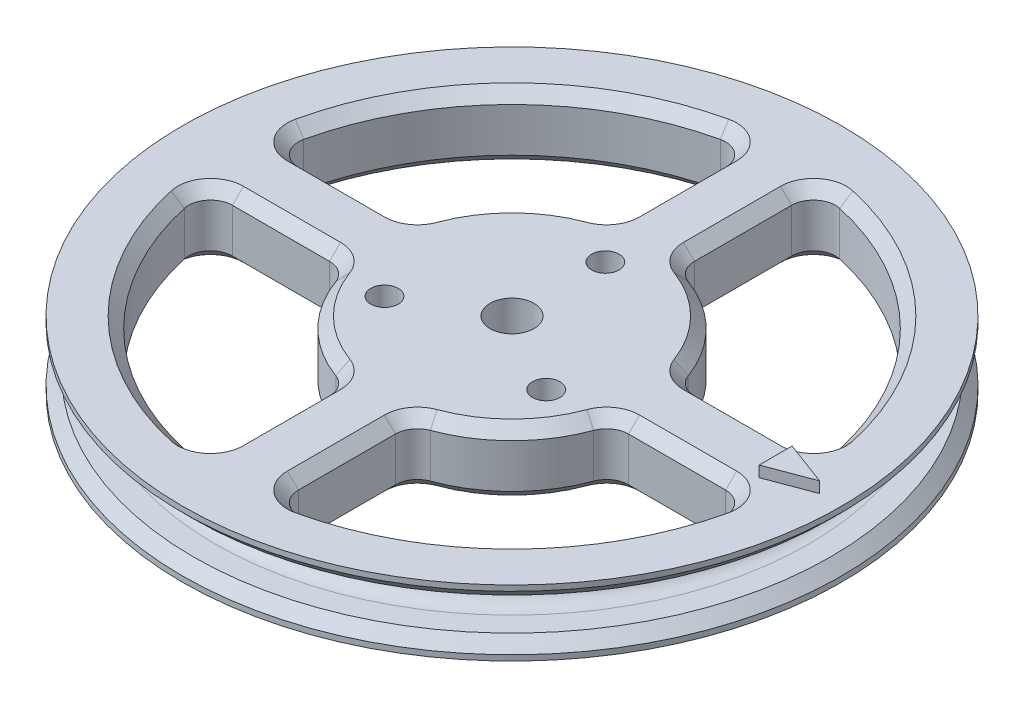
SolidWorks part; units mm, degrees
ref_plane "Front Plane" through (0, 0, 0) normal (0, 0, 1) x (1, 0, 0)
ref_plane "Top Plane" through (0, 0, 0) normal (0, 1, 0) x (1, 0, 0)
ref_plane "Right Plane" through (0, 0, 0) normal (1, 0, 0) x (0, 0, -1)
sketch "Sketch1" plane through (0, 0, 0) normal (0, 1, 0) x (1, 0, 0)
  line L0 (0, 0) -> (0, 36.3748) construction
  line L1 (0, 0) -> (-45.1254, 0) construction
  line L2 (-22.4499, -3) -> (-13.6107, -3)
  line L3 (-3, -22.4499) -> (-3, -13.6107)
  line L4 (3, -22.4499) -> (3, -13.6107)
  line L5 (22.4499, -3) -> (13.6107, -3)
  line L6 (22.4499, 3) -> (13.6107, 3)
  line L7 (3, 22.4499) -> (3, 13.6107)
  line L8 (-3, 22.4499) -> (-3, 13.6107)
  line L9 (-22.4499, 3) -> (-13.6107, 3)
  circle A0 centre (0, 0) radius 30
  circle A1 centre (0, 0) radius 8.5 construction
  circle A3 centre (0, 0) radius 2
  circle A4 centre (-7.3612, -4.25) radius 1.5 construction
  circle A5 centre (7.3612, -4.25) radius 1.5 construction
  circle A6 centre (0, 8.5) radius 1.5 construction
  arc A7 (-24.4021, -5.4348) -> (-5.4348, -24.4021) centre (0, 0) ccw
  arc A8 (-11.7333, -4.3103) -> (-4.3103, -11.7333) centre (0, 0) ccw
  arc A9 (0, -12.5) -> (-12.5, 0) centre (0, 0) ccw construction
  arc A10 (0, -25) -> (-25, 0) centre (0, 0) ccw construction
  arc A11 (-13.6107, -3) -> (-11.7333, -4.3103) centre (-13.6107, -5) cw
  arc A12 (-4.3103, -11.7333) -> (-3, -13.6107) centre (-5, -13.6107) cw
  arc A13 (-3, -22.4499) -> (-5.4348, -24.4021) centre (-5, -22.4499) cw
  arc A14 (-24.4021, -5.4348) -> (-22.4499, -3) centre (-22.4499, -5) cw
  arc A15 (24.4021, -5.4348) -> (5.4348, -24.4021) centre (0, 0) cw
  arc A16 (3, -22.4499) -> (5.4348, -24.4021) centre (5, -22.4499) ccw
  arc A17 (4.3103, -11.7333) -> (3, -13.6107) centre (5, -13.6107) ccw
  arc A18 (11.7333, -4.3103) -> (4.3103, -11.7333) centre (0, 0) cw
  arc A19 (13.6107, -3) -> (11.7333, -4.3103) centre (13.6107, -5) ccw
  arc A20 (24.4021, -5.4348) -> (22.4499, -3) centre (22.4499, -5) ccw
  arc A21 (24.4021, 5.4348) -> (22.4499, 3) centre (22.4499, 5) cw
  arc A22 (13.6107, 3) -> (11.7333, 4.3103) centre (13.6107, 5) cw
  arc A23 (11.7333, 4.3103) -> (4.3103, 11.7333) centre (0, 0) ccw
  arc A24 (4.3103, 11.7333) -> (3, 13.6107) centre (5, 13.6107) cw
  arc A25 (3, 22.4499) -> (5.4348, 24.4021) centre (5, 22.4499) cw
  arc A26 (24.4021, 5.4348) -> (5.4348, 24.4021) centre (0, 0) ccw
  arc A27 (-24.4021, 5.4348) -> (-5.4348, 24.4021) centre (0, 0) cw
  arc A28 (-3, 22.4499) -> (-5.4348, 24.4021) centre (-5, 22.4499) ccw
  arc A29 (-4.3103, 11.7333) -> (-3, 13.6107) centre (-5, 13.6107) ccw
  arc A30 (-11.7333, 4.3103) -> (-4.3103, 11.7333) centre (0, 0) cw
  arc A31 (-13.6107, 3) -> (-11.7333, 4.3103) centre (-13.6107, 5) ccw
  arc A32 (-24.4021, 5.4348) -> (-22.4499, 3) centre (-22.4499, 5) ccw
  point P4 (0, 8.5)
  point P5 (7.3612, -4.25)
  point P8 (-7.3612, -4.25)
  point P9 (0, 0)
  dimension "D1" = 60
  dimension "D2" = 17
  dimension "D4" = 4
  dimension "D5" = 3
  dimension "D6" = 50
  dimension "D7" = 25
  dimension "D10" = 2
  dimension "D8" = 3
  dimension "D9" = 3
  dimension "D3" = 3
extrude "Boss-Extrude1" add sketch "Sketch1" along normal blind 6
hole_wizard "M3x0.5 Tapped Hole1" positions "Sketch3" profile "Sketch4" tap size "M3x0.5" standard "ANSI Metric" end condition through all
sketch "Sketch3" plane through (0, 6, 0) normal (0, 1, 0) x (1, 0, 0)
  circle A0 centre (0, 0) radius 8.5 construction
  point P7 (0, 8.5)
  point P14 (7.3612, -4.25)
  point P15 (-7.3612, -4.25)
  dimension "D1" = 17
  dimension "D2" = 3
cosmetic thread "Hole Thread1" parameters "D2"=3
cosmetic thread "Hole Thread2" parameters "D2"=3
cosmetic thread "Hole Thread3" parameters "D2"=3
sketch "Sketch4" plane through (-7.3612, 6, 4.25) normal (1, 0, 0) x (0, 0, 1)
  line L0 (0, 0) -> (0, 6)
  line L1 (0, 6) -> (1.25, 6)
  line L2 (1.25, 6) -> (1.25, 0)
  line L5 (1.25, 0) -> (0, 0)
  line L11 (0, -6.35) -> (0, 107.95) construction
  dimension "Thru Tap Drill Dia." = 2.5
  dimension "Thru Tap Drill Depth" = 6
sketch "Sketch5" plane through (0, 0, 0) normal (1, 0, 0) x (0, 0, -1)
  line L0 (-30, 4.5) -> (-27, 4.5)
  line L1 (-30, 6) -> (-30, 0) construction
  line L2 (-30, 1.5) -> (-27, 1.5)
  line L3 (-30, 1.5) -> (-30, 4.5)
  line L4 (-30, 6) -> (-30, 3) construction
  line L5 (0, 0) -> (0, 13.1022) construction
  arc A1 (-27, 1.5) -> (-27, 4.5) centre (-27, 3) ccw
  point P9 (-30, 3)
  dimension "D3" = 3
  dimension "D1" = 3
  dimension "D2" = 3
revolve "Cut-Revolve1" cut sketch "Sketch5" angle 360 about L5
chamfer "Chamfer1" distance 1 angle 45 66 edges at (0, 1.5, -30) (0, 4.5, -30) (-8.8388, 0, -8.8388) (-3.36, 0, -12.466) (-12.466, 0, -3.36) (-3, 0, -18.0303) (-18.0303, 0, -3) (-3.7489, 0, -24.0103) (-24.0103, 0, -3.7489) (-17.6777, 0, -17.6777) (-8.8388, 0, 8.8388) (-12.466, 0, 3.36) (-3.36, 0, 12.466) (-18.0303, 0, 3) (-3, 0, 18.0303) (-24.0103, 0, 3.7489) (-3.7489, 0, 24.0103) (-17.6777, 0, 17.6777) (8.8388, 0, 8.8388) (3.36, 0, 12.466) (12.466, 0, 3.36) (3, 0, 18.0303) (18.0303, 0, 3) (3.7489, 0, 24.0103) (24.0103, 0, 3.7489) (17.6777, 0, 17.6777) (8.8388, 0, -8.8388) (12.466, 0, -3.36) (3.36, 0, -12.466) (18.0303, 0, -3) (3, 0, -18.0303) (24.0103, 0, -3.7489) (3.7489, 0, -24.0103) (17.6777, 0, -17.6777) (17.6777, 6, -17.6777) (3.7489, 6, -24.0103) (24.0103, 6, -3.7489) (3, 6, -18.0303) (18.0303, 6, -3) (3.36, 6, -12.466) (12.466, 6, -3.36) (8.8388, 6, -8.8388) (-17.6777, 6, -17.6777) (-24.0103, 6, -3.7489) (-3.7489, 6, -24.0103) (-18.0303, 6, -3) (-3, 6, -18.0303) (-12.466, 6, -3.36) (-3.36, 6, -12.466) (-8.8388, 6, -8.8388) (-8.8388, 6, 8.8388) (-12.466, 6, 3.36) (-3.36, 6, 12.466) (-18.0303, 6, 3) (-3, 6, 18.0303) (-24.0103, 6, 3.7489) (-3.7489, 6, 24.0103) (-17.6777, 6, 17.6777) (8.8388, 6, 8.8388) (3.36, 6, 12.466) (12.466, 6, 3.36) (3, 6, 18.0303) (18.0303, 6, 3) (3.7489, 6, 24.0103) (24.0103, 6, 3.7489) (17.6777, 6, 17.6777)
sketch "Sketch6" plane through (0, 6, 0) normal (0, 1, 0) x (1, 0, 0)
  line L0 (24, -1.5) -> (24, 1.5)
  line L1 (24, 1.5) -> (28, 0)
  line L2 (24, -1.5) -> (28, 0)
  point P2 (24, 0)
  point P5 (0, 0)
  point P7 (26.0291, 0)
  dimension "D1" = 3
  dimension "D2" = 4
  dimension "D3" = 24
extrude "Boss-Extrude2" add sketch "Sketch6" along normal blind 1
